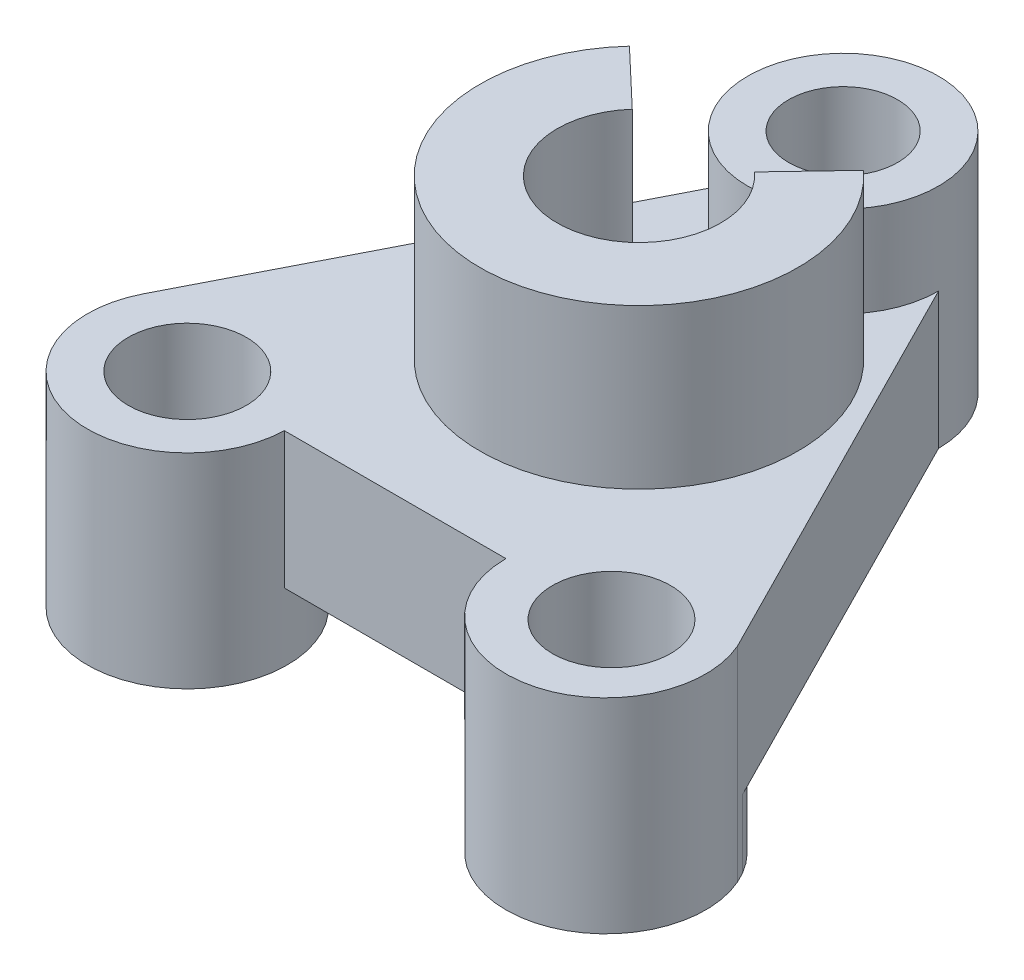
SolidWorks part; units mm, degrees
ref_plane "Front Plane" through (0, 0, 0) normal (0, 0, 1) x (1, 0, 0)
ref_plane "Top Plane" through (0, 0, 0) normal (0, 1, 0) x (1, 0, 0)
ref_plane "Right Plane" through (0, 0, 0) normal (1, 0, 0) x (0, 0, -1)
sketch "Sketch2" plane through (0, 0, 0) normal (0, 1, 0) x (1, 0, 0)
  line L0 (-108.7207, -4.4928) -> (-63.7482, 83.4945)
  line L1 (-67.1401, -15.1279) -> (-18.3562, -15.1279)
  line L2 (23.793, -6.2957) -> (-21.7482, 83.4945)
  line L3 (-111.1313, -14.5055) -> (27.957, -14.5055) construction
  line L4 (-63.7482, 83.4945) -> (-21.7482, 83.4945) construction
  arc A0 (-108.7207, -4.4928) -> (-67.1401, -15.1279) centre (-89.1313, -14.5055) ccw
  arc A1 (-18.3562, -15.1279) -> (22.6736, -4.0886) centre (3.6438, -15.1279) ccw
  circle A2 centre (-42.7482, 83.4945) radius 21
  circle A3 centre (-89.1313, -14.5055) radius 13
  circle A4 centre (4.8841, -15.1279) radius 13
  point P17 (-42.7482, -15.1279)
  dimension "D2" = 22
  dimension "D3" = 22
  dimension "D4" = 42
  dimension "D1" = 98
extrude "Boss-Extrude1" add sketch "Sketch2" against normal blind 30 contours A2 L0 A0 L1 A1 L2 A4 A3
sketch "Sketch3" plane through (0, 0, 0) normal (0, 1, 0) x (1, 0, 0)
  line L0 (-63.7482, 83.4945) -> (-21.7482, 83.4945) construction
  line L1 (-108.7207, -4.4928) -> (-63.7482, 83.4945) construction
  line L2 (23.793, -6.2957) -> (-21.7482, 83.4945) construction
  circle A1 centre (-42.7482, 83.4945) radius 12
  arc A2 (-63.7482, 83.4945) -> (-21.7482, 83.4945) centre (-42.7482, 83.4945) ccw construction
  circle A3 centre (-42.7482, 83.4945) radius 21
extrude "Boss-Extrude3" add sketch "Sketch3" against normal blind 30
sketch "Sketch4" plane through (0, 0, 0) normal (0, 1, 0) x (1, 0, 0)
  circle A0 centre (-42.7482, 83.4945) radius 21
extrude "Boss-Extrude4" add sketch "Sketch4" along normal blind 20
sketch "Sketch6" plane through (0, 0, 0) normal (0, 1, 0) x (1, 0, 0)
  circle A0 centre (-42.7482, 83.4945) radius 12
extrude "Cut-Extrude3" cut sketch "Sketch6" along normal blind 20
sketch "Sketch7" plane through (0, 0, 0) normal (0, 1, 0) x (1, 0, 0)
  line L0 (-55.1371, 49.4624) -> (-67.4711, 61.1681)
  line L1 (-29.7242, 50.9396) -> (-18.0185, 63.2736)
  arc A0 (-67.4711, 61.1681) -> (-18.0185, 63.2736) centre (-41.6921, 37.4945) ccw
  arc A1 (-55.1371, 49.4624) -> (-29.7242, 50.9396) centre (-41.6921, 37.4945) ccw
  point P5 (-61.3041, 55.3153)
  dimension "D2" = 35
  dimension "D3" = 18
  dimension "D1" = 46
extrude "Boss-Extrude5" add sketch "Sketch7" along normal blind 35
sketch "Sketch8" plane through (0, -30, 0) normal (0, -1, 0) x (1, 0, 0)
  line L0 (-67.1401, 15.1279) -> (-18.3562, 15.1279)
  circle A0 centre (-89.1313, 14.5055) radius 22
  circle A1 centre (3.6438, 15.1279) radius 22
  circle M3 centre (4.8841, 15.1279) radius 13
  circle M4 centre (-89.1313, 14.5055) radius 13
  line M7 (-21.7482, -83.4945) -> (23.793, 6.2957)
  arc M8 (23.793, 6.2957) -> (-18.3562, 15.1279) centre (3.6438, 15.1279) ccw
  arc M10 (-67.1401, 15.1279) -> (-108.7207, 4.4928) centre (-89.1313, 14.5055) ccw
extrude "Boss-Extrude6" add sketch "Sketch8" along normal blind 15 contours A1 M8 M7 M3 | A0 M10 M4
